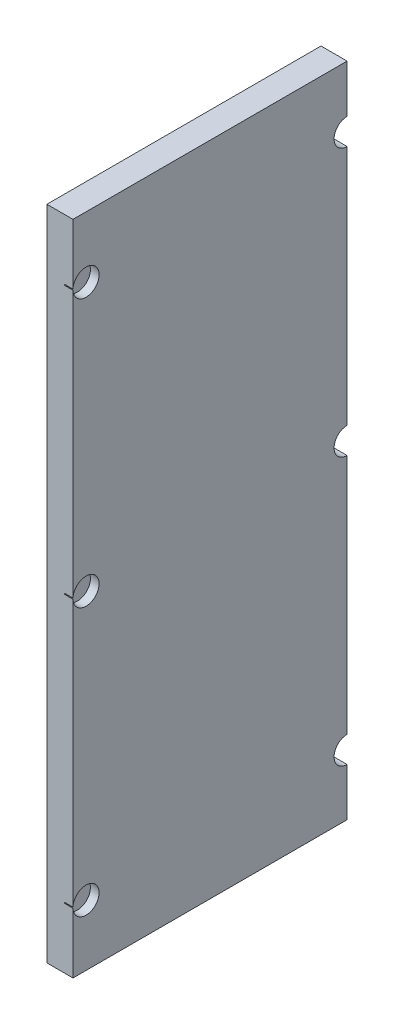
SolidWorks part; units mm, degrees
ref_plane "Спереди" through (0, 0, 0) normal (0, 0, 1) x (1, 0, 0)
ref_plane "Сверху" through (0, 0, 0) normal (0, 1, 0) x (1, 0, 0)
ref_plane "Справа" through (0, 0, 0) normal (1, 0, 0) x (0, 0, -1)
other "Configuration Table"
sketch "Эскиз1" plane through (0, 0, 0) normal (0, 0, 1) x (1, 0, 0)
  line L1 (0, 0) -> (3, 0)
  line L2 (0, 0) -> (0, 74)
  line L3 (0, 74) -> (3, 74)
  line L4 (3, 0) -> (3, 74)
extrude "Бобышка-Вытянуть1" add sketch "Эскиз1" along normal blind 31.5
sketch "Эскиз2" plane through (0, 0, 0) normal (0, 0, 1) x (1, 0, 0)
  line L1 (0, 74) -> (3, 74)
  line L2 (0, 74) -> (0, 75.5)
  line L3 (0, 75.5) -> (3, 75.5)
  line L4 (3, 74) -> (3, 75.5)
extrude "side_rear_extension_1p5mm" add sketch "Эскиз2" along normal blind 31.5
sketch "Эскиз3" plane through (3, 0, 0) normal (1, 0, 0) x (0, 0, -1)
  circle A0 centre (-30.001, 7) radius 1.5
  circle A1 centre (-30.001, 37.75) radius 1.5
  circle A2 centre (-30.001, 68.5) radius 1.5
extrude "side_top_edge_magnet_pockets_D3_depth1_3x" cut sketch "Эскиз3" against normal blind 1
sketch "Эскиз4" plane through (0, 0, 0) normal (-1, 0, 0) x (0, 0, 1)
  line L0 (0, 5.5) -> (0, 8.5)
  line L1 (0, 36.25) -> (0, 39.25)
  line L2 (0, 67) -> (0, 70)
  arc A0 (0, 5.5) -> (0, 8.5) centre (0, 7) ccw
  arc A1 (0, 36.25) -> (0, 39.25) centre (0, 37.75) ccw
  arc A2 (0, 67) -> (0, 70) centre (0, 68.5) ccw
extrude "side_bottom_edge_semicircles_D3_through_3x" cut sketch "Эскиз4" against normal blind 4
